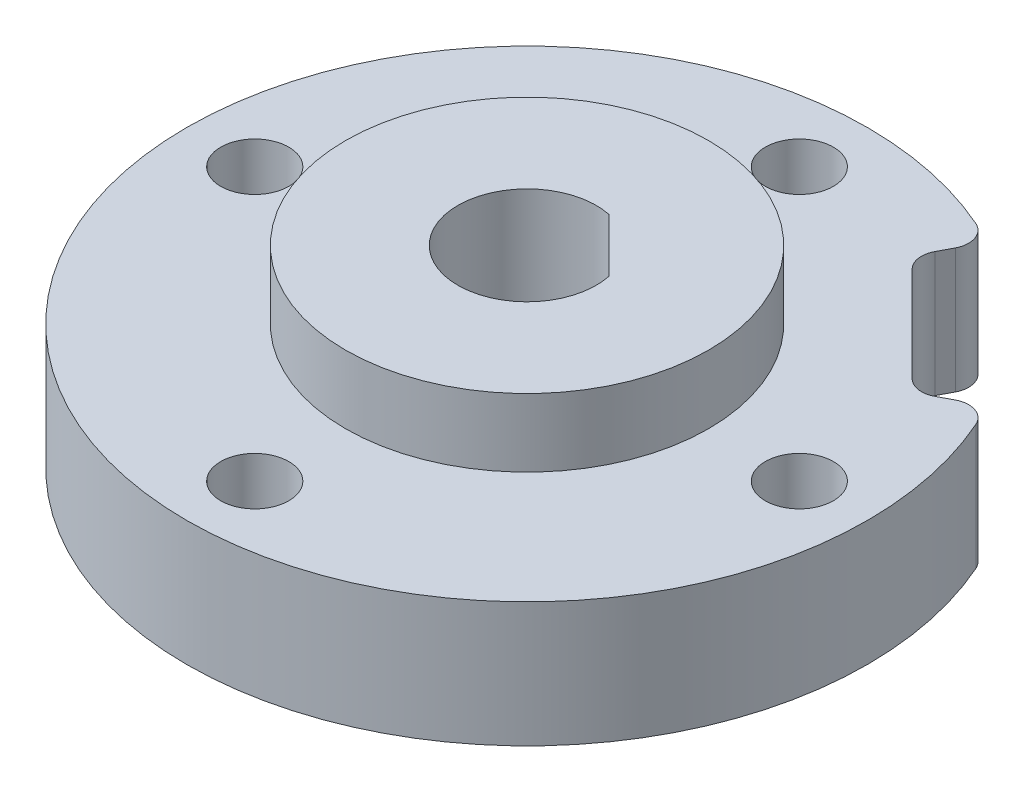
SolidWorks part; units mm, degrees
ref_plane "前视基准面" through (0, 0, 0) normal (0, 0, 1) x (1, 0, 0)
ref_plane "上视基准面" through (0, 0, 0) normal (0, 1, 0) x (1, 0, 0)
ref_plane "右视基准面" through (0, 0, 0) normal (1, 0, 0) x (0, 0, -1)
sketch "草图1" plane through (0, 0, 0) normal (0, 1, 0) x (1, 0, 0)
  line L0 (0, 0) -> (0, 18.2938) construction
  line L1 (0, 0) -> (19.7965, 0) construction
  circle A0 centre (0, 0) radius 6 construction
  circle A1 centre (0, 0) radius 12 construction
  circle A2 centre (0, 0) radius 2
  circle A3 centre (0, 6) radius 1.5
  circle A4 centre (6, 0) radius 1.5
  circle A5 centre (0, -6) radius 1.5
  circle A6 centre (-6, 0) radius 1.5
  circle A7 centre (0, 0) radius 15
  circle A8 centre (0, 12) radius 1.5
  circle A9 centre (12, 0) radius 1.5
  circle A10 centre (0, -12) radius 1.5
  circle A11 centre (-12, 0) radius 1.5
  point P16 (0, 0)
  point P28 (0, 0)
  dimension "D1" = 12
  dimension "D2" = 24
  dimension "D3" = 4
  dimension "D4" = 3
  dimension "D6" = 30
  dimension "D8" = 3
  dimension "D7" = 90
  dimension "D5" = 4
  dimension "D9" = 4
extrude "凸台-拉伸1" add sketch "草图1" along normal blind 3
sketch "草图2" plane through (0, 0, 0) normal (0, -1, 0) x (1, 0, 0)
  circle A0 centre (0, 0) radius 8
  dimension "D1" = 16
extrude "凸台-拉伸2" add sketch "草图2" along normal blind 4.25 and the other way blind 7.25
sketch "草图5" plane through (0, 3, 0) normal (0, 1, 0) x (1, 0, 0)
  circle A4 centre (0, 0) radius 15
extrude "凸台-拉伸3" add sketch "草图5" along normal blind 1.25 and the other way blind 4.25
sketch "草图3" plane through (0, 3, 0) normal (0, 1, 0) x (1, 0, 0)
  line L1 (0.6199, 2.9863) -> (2.9863, 0.6199)
  line L2 (0, 0) -> (3.05, 0) construction
  arc A1 (0.6199, 2.9863) -> (2.9863, 0.6199) centre (0, 0) ccw
  dimension "D1" = 6.1
  dimension "D2" = 2.55
  dimension "D3" = 45
extrude "切除-拉伸1" cut sketch "草图3" against normal blind 16.5 and the other way blind 5
sketch "草图6" plane through (1.8031, 0, -1.8031) normal (-0.7071, 0, 0.7071) x (0.7071, 0, 0.7071)
  circle A0 centre (0, 1.5) radius 1.3
  dimension "D1" = 2.6
  dimension "D2" = 1.5
extrude "切除-拉伸2" cut sketch "草图6" against normal blind 14
sketch "草图7" plane through (0, 7.25, 0) normal (0, 1, 0) x (1, 0, 0)
  line L0 (0, 12) -> (0, -12) construction
  line L1 (-12, 0) -> (12, 0) construction
  circle A0 centre (0, 12) radius 1.5
  circle A1 centre (-12, 0) radius 1.5
  circle A2 centre (12, 0) radius 1.5
  circle A3 centre (0, -12) radius 1.5
  dimension "D3" = 3
  dimension "D4" = 3
  dimension "D5" = 3
  dimension "D6" = 3
  dimension "D1" = 24
  dimension "D2" = 24
extrude "切除-拉伸4" cut sketch "草图7" against normal blind 14
sketch "草图8" plane through (0, 4.25, 0) normal (0, 1, 0) x (1, 0, 0)
  line L0 (7.0202, 13.2558) -> (5.8758, 11.0948)
  line L1 (5.8758, 11.0948) -> (11.0948, 5.8758)
  line L2 (11.0948, 5.8758) -> (13.2558, 7.0202)
  line L3 (2.9863, 0.6199) -> (0.6199, 2.9863) construction
  line L4 (0, 0) -> (8.4853, 8.4853) construction
  circle A0 centre (0, 0) radius 15 construction
  arc A1 (7.0202, 13.2558) -> (13.2558, 7.0202) centre (0, 0) cw
  dimension "D1" = 12
extrude "切除-拉伸5" cut sketch "草图8" against normal blind 14
fillet "圆角1" radius 1 4 edges at (13.2558, 1.5, -7.0202) (7.0202, 1.5, -13.2558) (11.0948, 1.5, -5.8758) (5.8758, 1.5, -11.0948)
